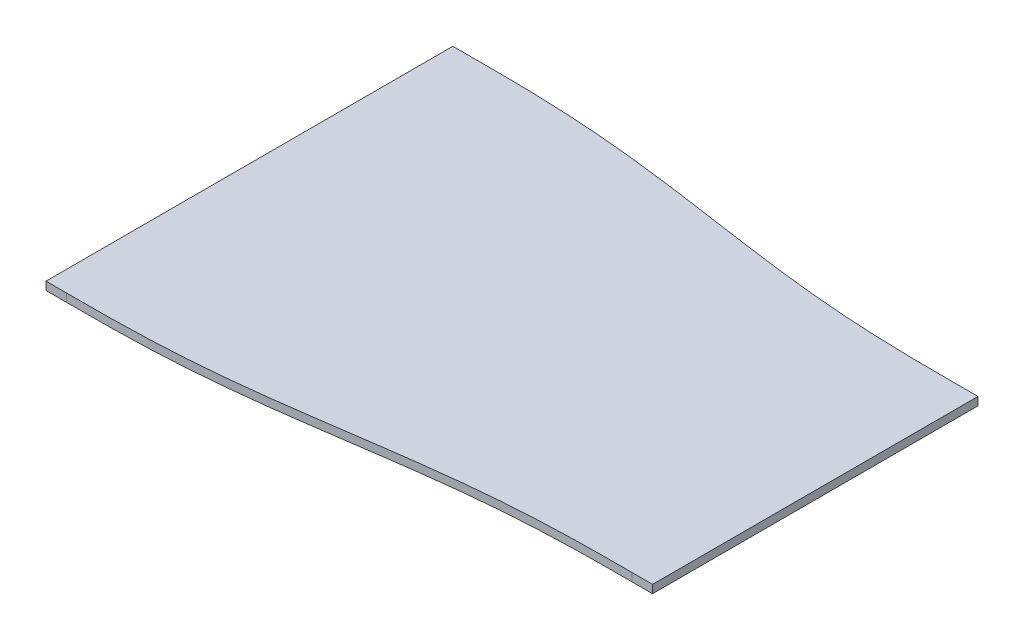
SolidWorks part; units mm, degrees
ref_plane "Front Plane" through (0, 0, 0) normal (0, 0, 1) x (1, 0, 0)
ref_plane "Top Plane" through (0, 0, 0) normal (0, 1, 0) x (1, 0, 0)
ref_plane "Right Plane" through (0, 0, 0) normal (1, 0, 0) x (0, 0, -1)
sketch "Sketch2" plane through (0, 0, 0) normal (0, 1, 0) x (1, 0, 0)
  line L3 (644.65, -200) -> (670.05, -200)
  line L5 (644.65, 200) -> (670.05, 200)
  line L6 (670.05, -200) -> (670.05, 200)
  line L7 (0, -250) -> (-25.4, -250)
  line L9 (0, 250) -> (-25.4, 250)
  line L10 (-25.4, -250) -> (-25.4, 250)
  spline S0 degree 4 poles (-64.4652, 250.578) (-63.7464, 250.5578) (-62.3091, 250.5186) (-59.439, 250.4454) (-55.1195, 250.3501) (-50.8237, 250.2712) (-46.49, 250.2067) (-42.355, 250.1543) (-38.2524, 250.1123) (-33.7937, 250.0747) (-28.3389, 250.0442) (-23.6241, 250.0234) (-17.6708, 250.0104) (-12.5924, 250.0016) (-1.3202, 249.9991) (2.4342, 250.0011) (15.0165, 249.9975) (20.3963, 249.9848) (27.7036, 249.9668) (32.9584, 249.939) (39.469, 249.8996) (45.354, 249.8461) (51.6977, 249.7762) (59.5778, 249.6651) (72.0554, 249.4387) (88.9384, 249.0002) (110.2771, 248.1779) (134.4228, 246.851) (158.5503, 245.1185) (182.6417, 242.9908) (208.6469, 240.2946) (234.6073, 237.211) (260.5296, 233.8162) (286.4211, 230.2022) (310.359, 226.7466) (334.291, 223.2534) (358.2288, 219.7978) (384.1205, 216.1838) (410.0425, 212.789) (433.0011, 210.062) (452.9862, 207.9446) (471.0422, 206.2113) (489.1171, 204.665) (510.2241, 203.149) (531.3592, 201.9879) (549.4786, 201.2397) (564.7781, 200.7645) (575.6152, 200.5064) (585.0771, 200.3349) (592.9503, 200.2238) (599.2934, 200.1539) (605.1899, 200.1004) (611.6737, 200.061) (616.9772, 200.0332) (624.2068, 200.0152) (629.7128, 200.0025) (642.0991, 199.9989) (646.7524, 200.0012) (659.6897, 199.9977) (664.0735, 199.9857) (669.5147, 199.9709) (671.8054, 199.9604) (675.12, 199.9444) (678.9909, 199.92) (683.6735, 199.8819) (689.1374, 199.8221) (694.7461, 199.742) (700.4935, 199.6367) (704.8048, 199.5381) (707.6782, 199.4624) (709.115, 199.422) knots 0 0 0 0 0 0.003703 0.007405 0.014811 0.022216 0.025919 0.029622 0.036299 0.042977 0.049654 0.056332 0.06301 0.069687 0.083042 0.098619 0.106407 0.114196 0.121984 0.129772 0.13756 0.145349 0.153608 0.161867 0.178385 0.209538 0.240692 0.271845 0.302998 0.334151 0.365305 0.40654 0.437694 0.468847 0.5 0.531153 0.562306 0.59346 0.634695 0.665849 0.681425 0.697002 0.728155 0.759308 0.790462 0.806038 0.821615 0.838133 0.846392 0.854651 0.86244 0.870228 0.878016 0.885804 0.893593 0.901381 0.916958 0.930313 0.943668 0.947007 0.950346 0.953684 0.957023 0.963701 0.970378 0.977784 0.985189 0.992595 1 1 1 1 1 construction
  spline S1 degree 4 poles (0, 250) (2.5211, 250) (6.2096, 250) (15.0165, 249.9975) (20.3963, 249.9848) (27.7036, 249.9668) (32.9584, 249.939) (39.469, 249.8996) (45.354, 249.8461) (51.6977, 249.7762) (59.5778, 249.6651) (72.0554, 249.4387) (88.9384, 249.0002) (110.2771, 248.1779) (134.4228, 246.851) (158.5503, 245.1185) (182.6417, 242.9908) (208.6469, 240.2946) (234.6073, 237.211) (260.5296, 233.8162) (286.4211, 230.2022) (310.359, 226.7466) (334.291, 223.2534) (358.2288, 219.7978) (384.1205, 216.1838) (410.0425, 212.789) (433.0011, 210.062) (452.9862, 207.9446) (471.0422, 206.2113) (489.1171, 204.665) (510.2241, 203.149) (531.3592, 201.9879) (549.4786, 201.2397) (564.7781, 200.7645) (575.6152, 200.5064) (585.0771, 200.3349) (592.9503, 200.2238) (599.2934, 200.1539) (605.1899, 200.1004) (611.6737, 200.061) (616.9772, 200.0332) (624.2068, 200.0152) (629.7128, 200.0025) (638.3825, 200) (642.1289, 200) (644.65, 200) knots 0.083042 0.083042 0.083042 0.083042 0.083042 0.098619 0.106407 0.114196 0.121984 0.129772 0.13756 0.145349 0.153608 0.161867 0.178385 0.209538 0.240692 0.271845 0.302998 0.334151 0.365305 0.40654 0.437694 0.468847 0.5 0.531153 0.562306 0.59346 0.634695 0.665849 0.681425 0.697002 0.728155 0.759308 0.790462 0.806038 0.821615 0.838133 0.846392 0.854651 0.86244 0.870228 0.878016 0.885804 0.893593 0.901381 0.916958 0.916958 0.916958 0.916958 0.916958
  spline S2 degree 4 poles (-64.4652, -250.578) (-63.7464, -250.5578) (-62.3091, -250.5186) (-59.439, -250.4454) (-55.1195, -250.3501) (-50.8237, -250.2712) (-46.49, -250.2067) (-42.355, -250.1543) (-38.2524, -250.1123) (-33.7937, -250.0747) (-28.3389, -250.0442) (-23.6241, -250.0234) (-17.6708, -250.0104) (-12.5924, -250.0016) (-1.3202, -249.9991) (2.4342, -250.0011) (15.0165, -249.9975) (20.3963, -249.9848) (27.7036, -249.9668) (32.9584, -249.939) (39.469, -249.8996) (45.354, -249.8461) (51.6977, -249.7762) (59.5778, -249.6651) (72.0554, -249.4387) (88.9384, -249.0002) (110.2771, -248.1779) (134.4228, -246.851) (158.5503, -245.1185) (182.6417, -242.9908) (208.6469, -240.2946) (234.6073, -237.211) (260.5296, -233.8162) (286.4211, -230.2022) (310.359, -226.7466) (334.291, -223.2534) (358.2288, -219.7978) (384.1205, -216.1838) (410.0425, -212.789) (433.0011, -210.062) (452.9862, -207.9446) (471.0422, -206.2113) (489.1171, -204.665) (510.2241, -203.149) (531.3592, -201.9879) (549.4786, -201.2397) (564.7781, -200.7645) (575.6152, -200.5064) (585.0771, -200.3349) (592.9503, -200.2238) (599.2934, -200.1539) (605.1899, -200.1004) (611.6737, -200.061) (616.9772, -200.0332) (624.2068, -200.0152) (629.7128, -200.0025) (642.0991, -199.9989) (646.7524, -200.0012) (659.6897, -199.9977) (664.0735, -199.9857) (669.5147, -199.9709) (671.8054, -199.9604) (675.12, -199.9444) (678.9909, -199.92) (683.6735, -199.8819) (689.1374, -199.8221) (694.7461, -199.742) (700.4935, -199.6367) (704.8048, -199.5381) (707.6782, -199.4624) (709.115, -199.422) knots 0 0 0 0 0 0.003703 0.007405 0.014811 0.022216 0.025919 0.029622 0.036299 0.042977 0.049654 0.056332 0.06301 0.069687 0.083042 0.098619 0.106407 0.114196 0.121984 0.129772 0.13756 0.145349 0.153608 0.161867 0.178385 0.209538 0.240692 0.271845 0.302998 0.334151 0.365305 0.40654 0.437694 0.468847 0.5 0.531153 0.562306 0.59346 0.634695 0.665849 0.681425 0.697002 0.728155 0.759308 0.790462 0.806038 0.821615 0.838133 0.846392 0.854651 0.86244 0.870228 0.878016 0.885804 0.893593 0.901381 0.916958 0.930313 0.943668 0.947007 0.950346 0.953684 0.957023 0.963701 0.970378 0.977784 0.985189 0.992595 1 1 1 1 1 construction
  spline S3 degree 4 poles (0, -250) (2.5211, -250) (6.2096, -250) (15.0165, -249.9975) (20.3963, -249.9848) (27.7036, -249.9668) (32.9584, -249.939) (39.469, -249.8996) (45.354, -249.8461) (51.6977, -249.7762) (59.5778, -249.6651) (72.0554, -249.4387) (88.9384, -249.0002) (110.2771, -248.1779) (134.4228, -246.851) (158.5503, -245.1185) (182.6417, -242.9908) (208.6469, -240.2946) (234.6073, -237.211) (260.5296, -233.8162) (286.4211, -230.2022) (310.359, -226.7466) (334.291, -223.2534) (358.2288, -219.7978) (384.1205, -216.1838) (410.0425, -212.789) (433.0011, -210.062) (452.9862, -207.9446) (471.0422, -206.2113) (489.1171, -204.665) (510.2241, -203.149) (531.3592, -201.9879) (549.4786, -201.2397) (564.7781, -200.7645) (575.6152, -200.5064) (585.0771, -200.3349) (592.9503, -200.2238) (599.2934, -200.1539) (605.1899, -200.1004) (611.6737, -200.061) (616.9772, -200.0332) (624.2068, -200.0152) (629.7128, -200.0025) (638.3825, -200) (642.1289, -200) (644.65, -200) knots 0.083042 0.083042 0.083042 0.083042 0.083042 0.098619 0.106407 0.114196 0.121984 0.129772 0.13756 0.145349 0.153608 0.161867 0.178385 0.209538 0.240692 0.271845 0.302998 0.334151 0.365305 0.40654 0.437694 0.468847 0.5 0.531153 0.562306 0.59346 0.634695 0.665849 0.681425 0.697002 0.728155 0.759308 0.790462 0.806038 0.821615 0.838133 0.846392 0.854651 0.86244 0.870228 0.878016 0.885804 0.893593 0.901381 0.916958 0.916958 0.916958 0.916958 0.916958
  dimension "D1" = 25.4
  dimension "D2" = 25.4
extrude "Boss-Extrude1" add sketch "Sketch2" along normal blind 10
